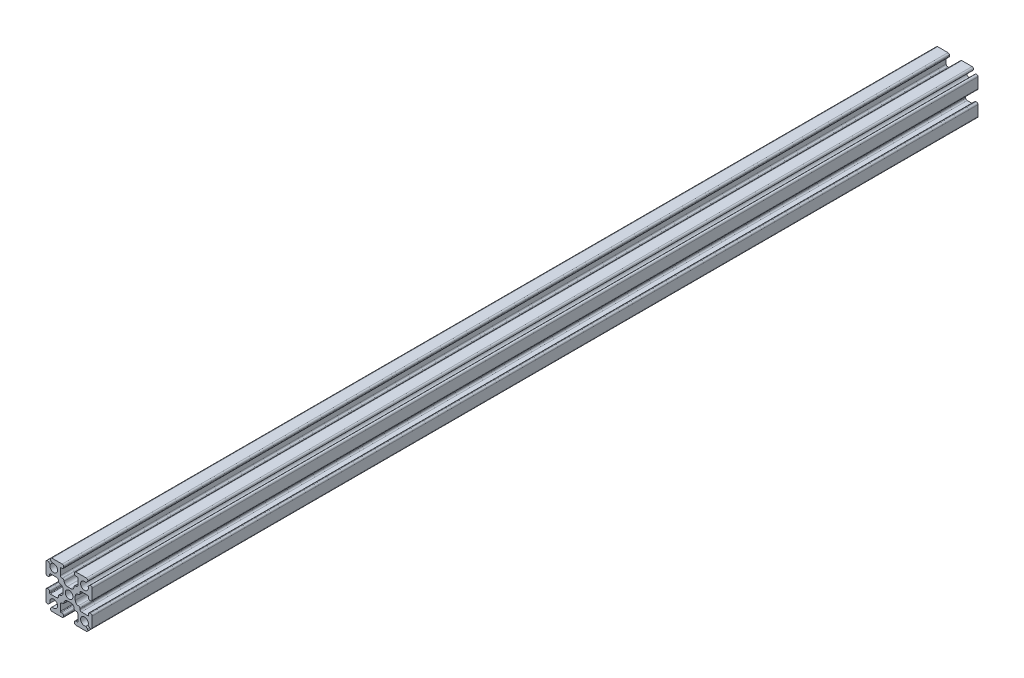
SolidWorks part; units mm, degrees
ref_plane "Front" through (0, 0, 0) normal (0, 0, 1) x (1, 0, 0)
ref_plane "Top" through (0, 0, 0) normal (0, 1, 0) x (1, 0, 0)
ref_plane "Right" through (0, 0, 0) normal (1, 0, 0) x (0, 0, -1)
sketch "Sketch1" plane through (0, 0, 0) normal (0, 0, 1) x (1, 0, 0)
  line L0 (6.6464, 5.9393) -> (6.1636, 5.4565)
  line L1 (5.4565, 6.1636) -> (5.9393, 6.6464)
  line L2 (5.5858, 7.5) -> (2.25, 7.5)
  line L3 (1.75, 7) -> (1.75, 6.8)
  line L4 (2.25, 6.3) -> (2.65, 6.3)
  line L5 (2.85, 6.1) -> (2.85, 4)
  line L6 (2.35, 3.5) -> (2.1, 3.5)
  line L7 (0.6, 2) -> (-0.6, 2)
  line L8 (-2.1, 3.5) -> (-2.35, 3.5)
  line L9 (-2.85, 4) -> (-2.85, 6.1)
  line L10 (-2.65, 6.3) -> (-2.25, 6.3)
  line L11 (-1.75, 6.8) -> (-1.75, 7)
  line L12 (-2.25, 7.5) -> (-5.5858, 7.5)
  line L13 (-5.9393, 6.6464) -> (-5.4565, 6.1636)
  line L14 (-6.1636, 5.4565) -> (-6.6464, 5.9393)
  line L15 (-7.5, 5.5858) -> (-7.5, 2.25)
  line L16 (-7, 1.75) -> (-6.8, 1.75)
  line L17 (-6.3, 2.25) -> (-6.3, 2.65)
  line L18 (-6.1, 2.85) -> (-4, 2.85)
  line L19 (-3.5, 2.35) -> (-3.5, 2.1)
  line L20 (-2, 0.6) -> (-2, -0.6)
  line L21 (-3.5, -2.1) -> (-3.5, -2.35)
  line L22 (-4, -2.85) -> (-6.1, -2.85)
  line L23 (-6.3, -2.65) -> (-6.3, -2.25)
  line L24 (-6.8, -1.75) -> (-7, -1.75)
  line L25 (-7.5, -2.25) -> (-7.5, -5.5858)
  line L26 (-6.6464, -5.9393) -> (-6.1636, -5.4565)
  line L27 (-5.4565, -6.1636) -> (-5.9393, -6.6464)
  line L28 (-5.5858, -7.5) -> (-2.25, -7.5)
  line L29 (-1.75, -7) -> (-1.75, -6.8)
  line L30 (-2.25, -6.3) -> (-2.65, -6.3)
  line L31 (-2.85, -6.1) -> (-2.85, -4)
  line L32 (-2.35, -3.5) -> (-2.1, -3.5)
  line L33 (-0.6, -2) -> (0.6, -2)
  line L34 (2.1, -3.5) -> (2.35, -3.5)
  line L35 (2.85, -4) -> (2.85, -6.1)
  line L36 (2.65, -6.3) -> (2.25, -6.3)
  line L37 (1.75, -6.8) -> (1.75, -7)
  line L38 (2.25, -7.5) -> (5.5858, -7.5)
  line L39 (5.9393, -6.6464) -> (5.4565, -6.1636)
  line L40 (6.1636, -5.4565) -> (6.6464, -5.9393)
  line L41 (7.5, -5.5858) -> (7.5, -2.25)
  line L42 (7, -1.75) -> (6.8, -1.75)
  line L43 (6.3, -2.25) -> (6.3, -2.65)
  line L44 (6.1, -2.85) -> (4, -2.85)
  line L45 (3.5, -2.35) -> (3.5, -2.1)
  line L46 (2, -0.6) -> (2, 0.6)
  line L47 (3.5, 2.1) -> (3.5, 2.35)
  line L48 (4, 2.85) -> (6.1, 2.85)
  line L49 (6.3, 2.65) -> (6.3, 2.25)
  line L50 (6.8, 1.75) -> (7, 1.75)
  line L51 (7.5, 2.25) -> (7.5, 5.5858)
  circle A0 centre (0, 0) radius 1.25
  arc A1 (6.1636, 5.4565) -> (5.4565, 6.1636) centre (5, 5) cw
  arc A2 (5.9393, 6.6464) -> (5.5858, 7.5) centre (5.5858, 7) ccw
  arc A3 (2.25, 7.5) -> (1.75, 7) centre (2.25, 7) ccw
  arc A4 (1.75, 6.8) -> (2.25, 6.3) centre (2.25, 6.8) ccw
  arc A5 (2.65, 6.3) -> (2.85, 6.1) centre (2.65, 6.1) cw
  arc A6 (2.85, 4) -> (2.35, 3.5) centre (2.35, 4) cw
  arc A7 (2.1, 3.5) -> (1.6, 3) centre (2.1, 3) ccw
  arc A8 (1.6, 3) -> (0.6, 2) centre (0.6, 3) cw
  arc A9 (-0.6, 2) -> (-1.6, 3) centre (-0.6, 3) cw
  arc A10 (-1.6, 3) -> (-2.1, 3.5) centre (-2.1, 3) ccw
  arc A11 (-2.35, 3.5) -> (-2.85, 4) centre (-2.35, 4) cw
  arc A12 (-2.85, 6.1) -> (-2.65, 6.3) centre (-2.65, 6.1) cw
  arc A13 (-2.25, 6.3) -> (-1.75, 6.8) centre (-2.25, 6.8) ccw
  arc A14 (-1.75, 7) -> (-2.25, 7.5) centre (-2.25, 7) ccw
  arc A15 (-5.5858, 7.5) -> (-5.9393, 6.6464) centre (-5.5858, 7) ccw
  arc A16 (-5.4565, 6.1636) -> (-6.1636, 5.4565) centre (-5, 5) cw
  arc A17 (-6.6464, 5.9393) -> (-7.5, 5.5858) centre (-7, 5.5858) ccw
  arc A18 (-7.5, 2.25) -> (-7, 1.75) centre (-7, 2.25) ccw
  arc A19 (-6.8, 1.75) -> (-6.3, 2.25) centre (-6.8, 2.25) ccw
  arc A20 (-6.3, 2.65) -> (-6.1, 2.85) centre (-6.1, 2.65) cw
  arc A21 (-4, 2.85) -> (-3.5, 2.35) centre (-4, 2.35) cw
  arc A22 (-3.5, 2.1) -> (-3, 1.6) centre (-3, 2.1) ccw
  arc A23 (-3, 1.6) -> (-2, 0.6) centre (-3, 0.6) cw
  arc A24 (-2, -0.6) -> (-3, -1.6) centre (-3, -0.6) cw
  arc A25 (-3, -1.6) -> (-3.5, -2.1) centre (-3, -2.1) ccw
  arc A26 (-3.5, -2.35) -> (-4, -2.85) centre (-4, -2.35) cw
  arc A27 (-6.1, -2.85) -> (-6.3, -2.65) centre (-6.1, -2.65) cw
  arc A28 (-6.3, -2.25) -> (-6.8, -1.75) centre (-6.8, -2.25) ccw
  arc A29 (-7, -1.75) -> (-7.5, -2.25) centre (-7, -2.25) ccw
  arc A30 (-7.5, -5.5858) -> (-6.6464, -5.9393) centre (-7, -5.5858) ccw
  arc A31 (-6.1636, -5.4565) -> (-5.4565, -6.1636) centre (-5, -5) cw
  arc A32 (-5.9393, -6.6464) -> (-5.5858, -7.5) centre (-5.5858, -7) ccw
  arc A33 (-2.25, -7.5) -> (-1.75, -7) centre (-2.25, -7) ccw
  arc A34 (-1.75, -6.8) -> (-2.25, -6.3) centre (-2.25, -6.8) ccw
  arc A35 (-2.65, -6.3) -> (-2.85, -6.1) centre (-2.65, -6.1) cw
  arc A36 (-2.85, -4) -> (-2.35, -3.5) centre (-2.35, -4) cw
  arc A37 (-2.1, -3.5) -> (-1.6, -3) centre (-2.1, -3) ccw
  arc A38 (-1.6, -3) -> (-0.6, -2) centre (-0.6, -3) cw
  arc A39 (0.6, -2) -> (1.6, -3) centre (0.6, -3) cw
  arc A40 (1.6, -3) -> (2.1, -3.5) centre (2.1, -3) ccw
  arc A41 (2.35, -3.5) -> (2.85, -4) centre (2.35, -4) cw
  arc A42 (2.85, -6.1) -> (2.65, -6.3) centre (2.65, -6.1) cw
  arc A43 (2.25, -6.3) -> (1.75, -6.8) centre (2.25, -6.8) ccw
  arc A44 (1.75, -7) -> (2.25, -7.5) centre (2.25, -7) ccw
  arc A45 (5.5858, -7.5) -> (5.9393, -6.6464) centre (5.5858, -7) ccw
  arc A46 (5.4565, -6.1636) -> (6.1636, -5.4565) centre (5, -5) cw
  arc A47 (6.6464, -5.9393) -> (7.5, -5.5858) centre (7, -5.5858) ccw
  arc A48 (7.5, -2.25) -> (7, -1.75) centre (7, -2.25) ccw
  arc A49 (6.8, -1.75) -> (6.3, -2.25) centre (6.8, -2.25) ccw
  arc A50 (6.3, -2.65) -> (6.1, -2.85) centre (6.1, -2.65) cw
  arc A51 (4, -2.85) -> (3.5, -2.35) centre (4, -2.35) cw
  arc A52 (3.5, -2.1) -> (3, -1.6) centre (3, -2.1) ccw
  arc A53 (3, -1.6) -> (2, -0.6) centre (3, -0.6) cw
  arc A54 (2, 0.6) -> (3, 1.6) centre (3, 0.6) cw
  arc A55 (3, 1.6) -> (3.5, 2.1) centre (3, 2.1) ccw
  arc A56 (3.5, 2.35) -> (4, 2.85) centre (4, 2.35) cw
  arc A57 (6.1, 2.85) -> (6.3, 2.65) centre (6.1, 2.65) cw
  arc A58 (6.3, 2.25) -> (6.8, 1.75) centre (6.8, 2.25) ccw
  arc A59 (7, 1.75) -> (7.5, 2.25) centre (7, 2.25) ccw
  arc A60 (7.5, 5.5858) -> (6.6464, 5.9393) centre (7, 5.5858) ccw
extrude "Boss-Extrude1" add sketch "Sketch1" along normal blind 287.782
